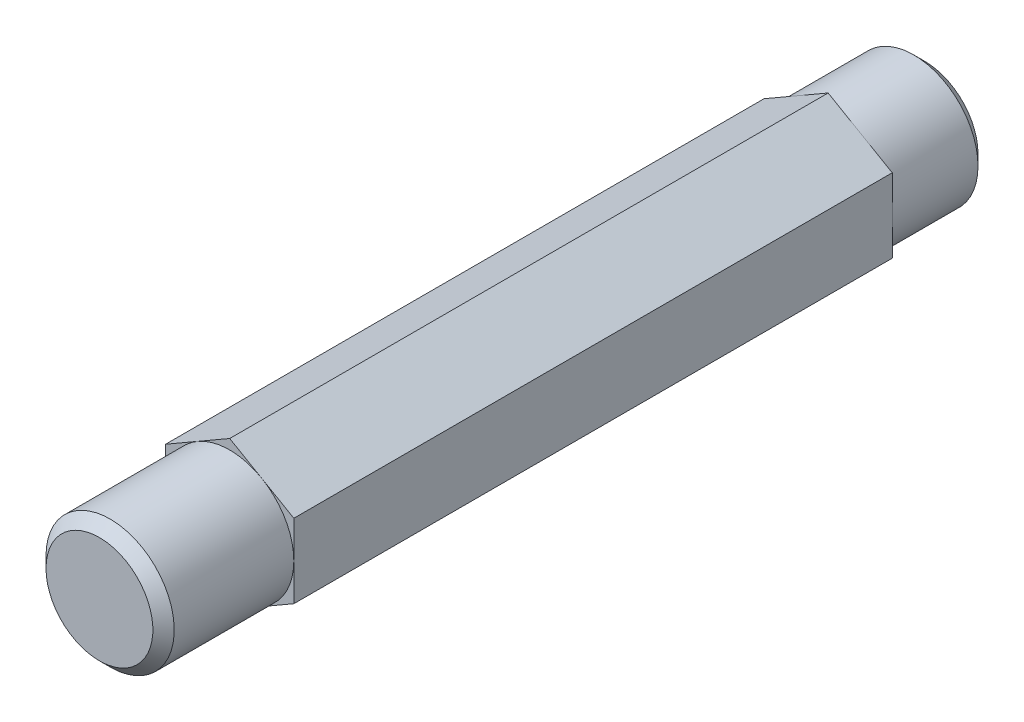
SolidWorks part; units mm, degrees
material "6061 Alloy"
ref_plane "Front Plane" through (0, 0, 0) normal (0, 0, 1) x (1, 0, 0)
ref_plane "Top Plane" through (0, 0, 0) normal (0, 1, 0) x (1, 0, 0)
ref_plane "Right Plane" through (0, 0, 0) normal (1, 0, 0) x (0, 0, -1)
sketch "Sketch1" plane through (0, 0, 0) normal (0, 0, 1) x (1, 0, 0)
  circle A0 centre (8.8615, 6.042) radius 4.7625
  dimension "D1" = 9.525
extrude "Boss-Extrude1" add sketch "Sketch1" against normal up to surface (7.1628 mm away)
sketch "Sketch2" plane through (0, 0, 0) normal (0, 0, 1) x (1, 0, 0)
  line L1 (13.624, 8.7916) -> (8.8615, 11.5412)
  line L2 (8.8615, 11.5412) -> (4.099, 8.7916)
  line L3 (4.099, 8.7916) -> (4.099, 3.2923)
  line L4 (4.099, 3.2923) -> (8.8615, 0.5427)
  line L5 (8.8615, 0.5427) -> (13.624, 3.2923)
  line L6 (13.624, 3.2923) -> (13.624, 8.7916)
  circle A0 centre (8.8615, 6.042) radius 4.7625 construction
  circle A1 centre (8.8615, 6.042) radius 4.7625 construction
extrude "Boss-Extrude2" add sketch "Sketch2" along normal blind 44.45
sketch "Sketch3" plane through (0, 0, 44.45) normal (0, 0, 1) x (1, 0, 0)
  circle A0 centre (8.8615, 6.042) radius 4.7625
  circle A1 centre (8.8615, 6.042) radius 4.7625 construction
extrude "Boss-Extrude3" add sketch "Sketch3" along normal up to surface (9.6774 mm away)
chamfer "Chamfer1" distance 0.7937 angle 45 2 edges at (8.8615, 10.8045, 54.1274) (13.624, 6.042, -7.1628)
